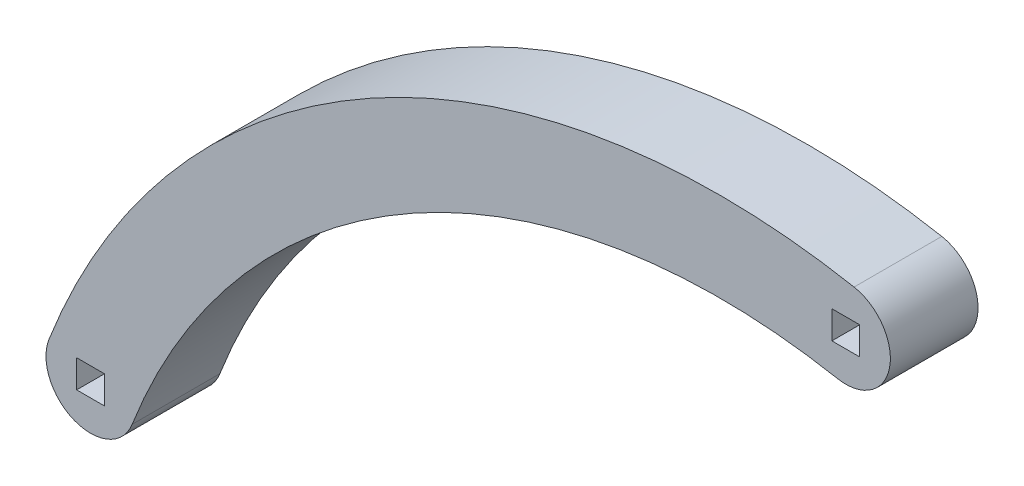
SolidWorks part; units mm, degrees
material "ABS"
ref_plane "Front Plane" through (0, 0, 0) normal (0, 0, 1) x (1, 0, 0)
ref_plane "Top Plane" through (0, 0, 0) normal (0, 1, 0) x (1, 0, 0)
ref_plane "Right Plane" through (0, 0, 0) normal (1, 0, 0) x (0, 0, -1)
sketch "Sketch1" plane through (0, 0, 0) normal (0, 0, 1) x (1, 0, 0)
  line L1 (-1.5875, -1.5875) -> (1.5875, -1.5875)
  line L2 (-1.5875, -1.5875) -> (-1.5875, 1.5875)
  line L3 (-1.5875, 1.5875) -> (1.5875, 1.5875)
  line L4 (1.5875, -1.5875) -> (1.5875, 1.5875)
  line L5 (-1.5875, -1.5875) -> (1.5875, 1.5875) construction
  line L6 (-1.5875, 1.5875) -> (1.5875, -1.5875) construction
  line L7 (84.5169, 46.3033) -> (87.6919, 46.3033)
  line L8 (84.5169, 46.3033) -> (84.5169, 49.4783)
  line L9 (84.5169, 49.4783) -> (87.6919, 49.4783)
  line L10 (87.6919, 46.3033) -> (87.6919, 49.4783)
  line L11 (84.5169, 46.3033) -> (87.6919, 49.4783) construction
  line L12 (84.5169, 49.4783) -> (87.6919, 46.3033) construction
  arc A0 (0, 0) -> (86.1044, 47.8908) centre (71.8042, -27.7488) cw construction
  arc A1 (87.0481, 52.8824) -> (-4.7385, 1.8312) centre (71.8042, -27.7488) ccw
  arc A2 (85.1607, 42.8992) -> (4.7385, -1.8312) centre (71.8042, -27.7488) ccw
  arc A3 (85.1607, 42.8992) -> (87.0481, 52.8824) centre (86.1044, 47.8908) ccw
  arc A4 (-4.7385, 1.8312) -> (4.7385, -1.8312) centre (0, 0) ccw
  point P3 (34.3868, 39.5251)
  point P9 (0, 0)
  point P14 (86.1044, 47.8908)
  dimension "D2" = 3.175
  dimension "D3" = 5.08
  dimension "D1" = 98.5266
extrude "Boss-Extrude1" add sketch "Sketch1" along normal blind 10
